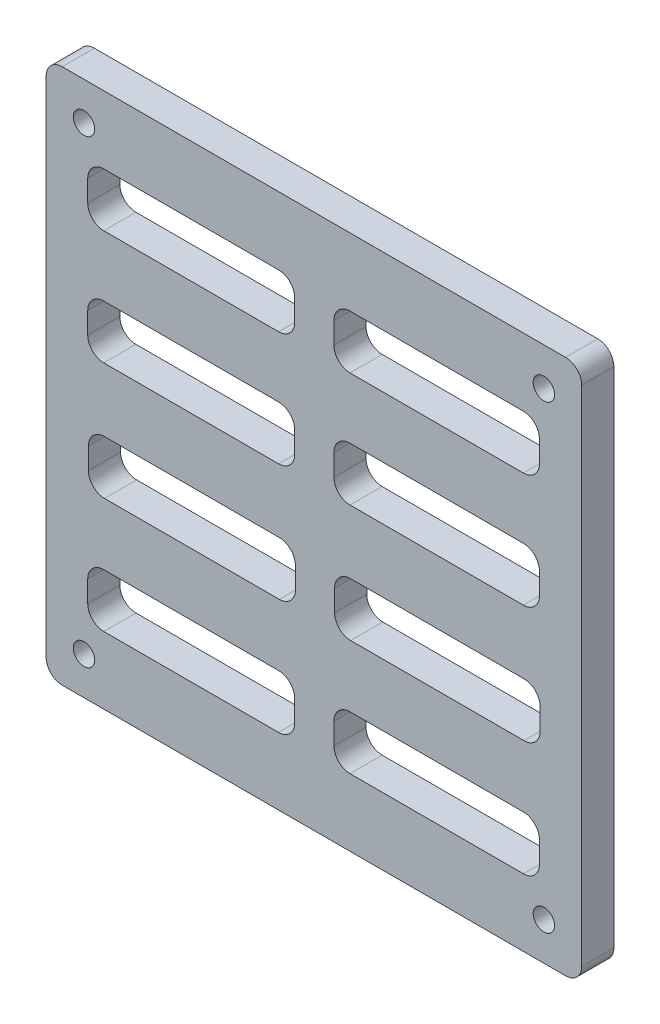
SolidWorks part; units mm, degrees
ref_plane "Alzado" through (0, 0, 0) normal (0, 0, 1) x (1, 0, 0)
ref_plane "Planta" through (0, 0, 0) normal (0, 1, 0) x (1, 0, 0)
ref_plane "Vista lateral" through (0, 0, 0) normal (1, 0, 0) x (0, 0, -1)
sketch "Croquis1" plane through (0, 0, 0) normal (0, 0, 1) x (1, 0, 0)
  line L1 (-94, -100) -> (94, -100)
  line L2 (-100, -94) -> (-100, 94)
  line L3 (-94, 100) -> (94, 100)
  line L4 (100, -94) -> (100, 94)
  line L7 (-5.0632, -100) -> (5.0632, -100)
  line L9 (-5.0632, 100) -> (5.0632, 100)
  line L14 (-100, -5.0632) -> (-100, 5.0632)
  line L16 (100, -5.0632) -> (100, 5.0632)
  line L25 (-78.475, 54.7082) -> (-13.195, 54.7082)
  line L26 (-84.475, 60.7082) -> (-84.475, 68.7082)
  line L27 (-78.475, 74.7082) -> (-13.195, 74.7082)
  line L28 (-7.195, 60.7082) -> (-7.195, 68.7082)
  line L31 (-78.475, 11.9848) -> (-13.195, 11.9848)
  line L32 (-84.475, 17.9848) -> (-84.475, 25.9848)
  line L33 (-78.475, 31.9848) -> (-13.195, 31.9848)
  line L34 (-7.195, 17.9848) -> (-7.195, 25.9848)
  line L37 (-78.2086, -31.7183) -> (-12.9286, -31.7183)
  line L38 (-84.2086, -25.7183) -> (-84.2086, -17.7183)
  line L39 (-78.2086, -11.7183) -> (-12.9286, -11.7183)
  line L40 (-6.9286, -25.7183) -> (-6.9286, -17.7183)
  line L43 (-78.475, -74.8886) -> (-13.195, -74.8886)
  line L44 (-84.475, -68.8886) -> (-84.475, -60.8886)
  line L45 (-78.475, -54.8886) -> (-13.195, -54.8886)
  line L46 (-7.195, -68.8886) -> (-7.195, -60.8886)
  line L49 (13.4615, 11.9848) -> (78.2086, 11.9848)
  line L50 (7.4615, 17.9848) -> (7.4615, 25.9848)
  line L51 (13.4615, 31.9848) -> (78.2086, 31.9848)
  line L52 (84.2086, 17.9848) -> (84.2086, 25.9848)
  line L53 (13.4615, 54.7082) -> (78.2086, 54.7082)
  line L54 (7.4615, 60.7082) -> (7.4615, 68.7082)
  line L55 (13.4615, 74.7082) -> (78.2086, 74.7082)
  line L56 (84.2086, 60.7082) -> (84.2086, 68.7082)
  line L57 (13.728, -31.7183) -> (78.475, -31.7183)
  line L58 (7.728, -25.7183) -> (7.728, -17.7183)
  line L59 (13.728, -11.7183) -> (78.475, -11.7183)
  line L60 (84.475, -25.7183) -> (84.475, -17.7183)
  line L61 (13.4615, -74.8886) -> (78.2086, -74.8886)
  line L62 (7.4615, -68.8886) -> (7.4615, -60.8886)
  line L63 (13.4615, -54.8886) -> (78.2086, -54.8886)
  line L64 (84.2086, -68.8886) -> (84.2086, -60.8886)
  circle A0 centre (-85.8741, 85.8741) radius 4
  circle A1 centre (85.8741, 85.8741) radius 4
  circle A2 centre (85.8741, -85.8741) radius 4
  circle A3 centre (-85.8741, -85.8741) radius 4
  arc A4 (94, 100) -> (100, 94) centre (94, 94) cw
  arc A5 (100, -94) -> (94, -100) centre (94, -94) cw
  arc A6 (-94, -100) -> (-100, -94) centre (-94, -94) cw
  arc A7 (-100, 94) -> (-94, 100) centre (-94, 94) cw
  arc A8 (-78.475, -74.8886) -> (-84.475, -68.8886) centre (-78.475, -68.8886) cw
  arc A9 (-84.475, -60.8886) -> (-78.475, -54.8886) centre (-78.475, -60.8886) cw
  arc A10 (-7.195, -60.8886) -> (-13.195, -54.8886) centre (-13.195, -60.8886) ccw
  arc A11 (-7.195, -68.8886) -> (-13.195, -74.8886) centre (-13.195, -68.8886) cw
  arc A12 (78.2086, -74.8886) -> (84.2086, -68.8886) centre (78.2086, -68.8886) ccw
  arc A13 (84.2086, -60.8886) -> (78.2086, -54.8886) centre (78.2086, -60.8886) ccw
  arc A14 (13.4615, -74.8886) -> (7.4615, -68.8886) centre (13.4615, -68.8886) cw
  arc A15 (7.4615, -60.8886) -> (13.4615, -54.8886) centre (13.4615, -60.8886) cw
  arc A16 (78.475, -31.7183) -> (84.475, -25.7183) centre (78.475, -25.7183) ccw
  arc A17 (84.475, -17.7183) -> (78.475, -11.7183) centre (78.475, -17.7183) ccw
  arc A18 (13.728, -31.7183) -> (7.728, -25.7183) centre (13.728, -25.7183) cw
  arc A19 (7.728, -17.7183) -> (13.728, -11.7183) centre (13.728, -17.7183) cw
  arc A20 (-84.2086, -17.7183) -> (-78.2086, -11.7183) centre (-78.2086, -17.7183) cw
  arc A21 (-84.2086, -25.7183) -> (-78.2086, -31.7183) centre (-78.2086, -25.7183) ccw
  arc A22 (-12.9286, -31.7183) -> (-6.9286, -25.7183) centre (-12.9286, -25.7183) ccw
  arc A23 (-6.9286, -17.7183) -> (-12.9286, -11.7183) centre (-12.9286, -17.7183) ccw
  arc A24 (-78.475, 11.9848) -> (-84.475, 17.9848) centre (-78.475, 17.9848) cw
  arc A25 (-84.475, 25.9848) -> (-78.475, 31.9848) centre (-78.475, 25.9848) cw
  arc A26 (-13.195, 11.9848) -> (-7.195, 17.9848) centre (-13.195, 17.9848) ccw
  arc A27 (-7.195, 25.9848) -> (-13.195, 31.9848) centre (-13.195, 25.9848) ccw
  arc A28 (78.2086, 11.9848) -> (84.2086, 17.9848) centre (78.2086, 17.9848) ccw
  arc A29 (84.2086, 25.9848) -> (78.2086, 31.9848) centre (78.2086, 25.9848) ccw
  arc A30 (13.4615, 11.9848) -> (7.4615, 17.9848) centre (13.4615, 17.9848) cw
  arc A31 (7.4615, 25.9848) -> (13.4615, 31.9848) centre (13.4615, 25.9848) cw
  arc A32 (-84.475, 68.7082) -> (-78.475, 74.7082) centre (-78.475, 68.7082) cw
  arc A33 (-84.475, 60.7082) -> (-78.475, 54.7082) centre (-78.475, 60.7082) ccw
  arc A34 (-13.195, 54.7082) -> (-7.195, 60.7082) centre (-13.195, 60.7082) ccw
  arc A35 (-7.195, 68.7082) -> (-13.195, 74.7082) centre (-13.195, 68.7082) ccw
  arc A36 (84.2086, 68.7082) -> (78.2086, 74.7082) centre (78.2086, 68.7082) ccw
  arc A37 (7.4615, 60.7082) -> (13.4615, 54.7082) centre (13.4615, 60.7082) ccw
  arc A38 (84.2086, 60.7082) -> (78.2086, 54.7082) centre (78.2086, 60.7082) cw
  arc A39 (7.4615, 68.7082) -> (13.4615, 74.7082) centre (13.4615, 68.7082) cw
  point P0 (0, 0)
  point P6 (0, 0)
  point P11 (0, 0)
  point P16 (0, 0)
  point P21 (-45.835, 64.7082)
  point P26 (-45.835, 30.5123)
  point P31 (-45.835, -29.4463)
  point P36 (-45.835, -64.8886)
  dimension "D1" = 6
  dimension "D2" = 6
  dimension "D3" = 6
  dimension "D4" = 6
  dimension "D5" = 6
  dimension "D6" = 6
  dimension "D7" = 6
  dimension "D8" = 6
  dimension "D9" = 6
  dimension "D10" = 6
  dimension "D11" = 6
  dimension "D12" = 6
  dimension "D13" = 6
  dimension "D14" = 6
  dimension "D15" = 6
  dimension "D16" = 6
  dimension "D17" = 6
  dimension "D18" = 6
  dimension "D19" = 6
  dimension "D20" = 6
  dimension "D21" = 6
  dimension "D22" = 6
  dimension "D23" = 6
  dimension "D24" = 6
  dimension "D25" = 6
  dimension "D26" = 6
  dimension "D27" = 6
  dimension "D28" = 6
  dimension "D29" = 6
  dimension "D30" = 6
  dimension "D31" = 6
  dimension "D32" = 6
  dimension "D33" = 6
  dimension "D34" = 6
  dimension "D35" = 6
  dimension "D36" = 6
extrude "Saliente-Extruir2" add sketch "Croquis1" along normal blind 10 and the other way blind 2 contours A7 L2 A6 L1 A5 L4 A4 L3 A35 L28 A34 L25 A33 L26 A32 L27 A27 L34 A26 L31 A24 L32 A25 L33 A23 L40 A22 L37 A21 L38 A20 L39 A3 A2 A1 A0
